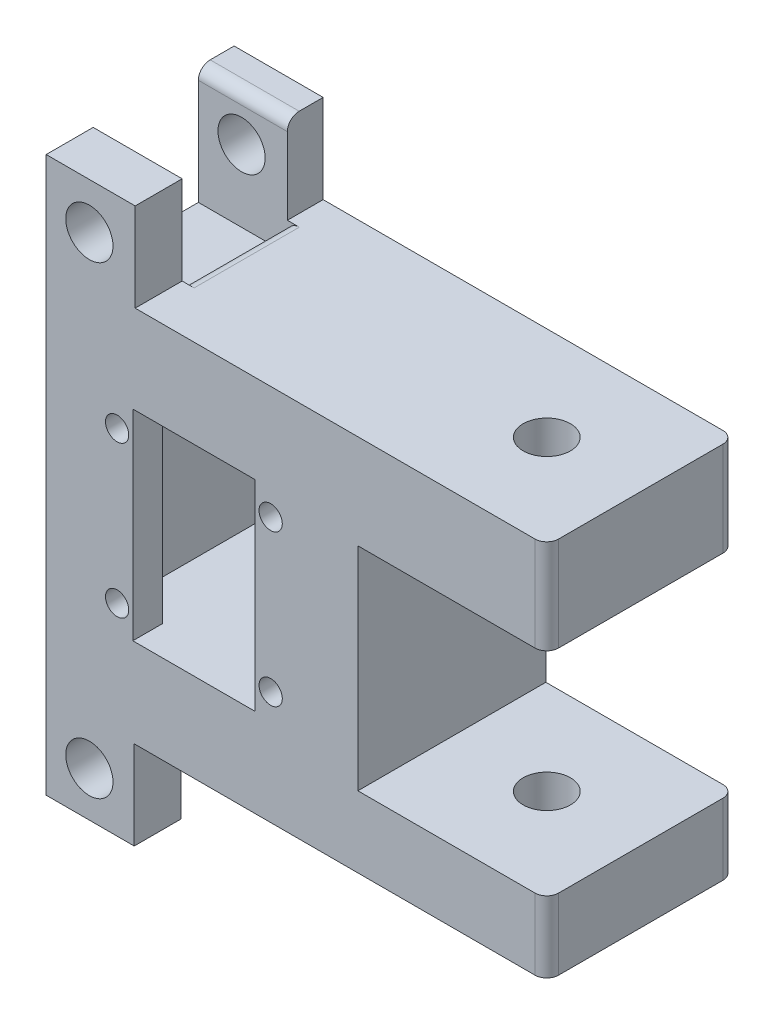
SolidWorks part; units mm, degrees
ref_plane "Front Plane" through (0, 0, 0) normal (0, 0, 1) x (1, 0, 0)
ref_plane "Top Plane" through (0, 0, 0) normal (0, 1, 0) x (1, 0, 0)
ref_plane "Right Plane" through (0, 0, 0) normal (1, 0, 0) x (0, 0, -1)
sketch "Sketch1" plane through (0, 0, 0) normal (0, 1, 0) x (1, 0, 0)
  line L1 (-53.8492, -20.2178) -> (53.8492, -20.2178)
  line L2 (-53.8492, -20.2178) -> (-53.8492, 20.2178)
  line L3 (-53.8492, 20.2178) -> (53.8492, 20.2178)
  line L4 (53.8492, -20.2178) -> (53.8492, 20.2178)
  line L5 (-53.8492, -20.2178) -> (53.8492, 20.2178) construction
  line L6 (-53.8492, 20.2178) -> (53.8492, -20.2178) construction
  point P0 (0, 0)
extrude "Boss-Extrude1" add sketch "Sketch1" along normal blind 55.88 and the other way blind 25.3849
sketch "Sketch7" plane through (0, 0, 20.2178) normal (0, 0, 1) x (1, 0, 0)
  line L0 (53.8492, 55.88) -> (0, -25.3849)
  line L1 (-53.8492, -25.3849) -> (53.8492, -25.3849) construction
  line L2 (0, -25.3849) -> (-53.8492, 55.88)
  line L3 (-53.8492, 55.88) -> (0, 55.88)
  line L4 (-53.8492, 55.88) -> (53.8492, 55.88) construction
  line L5 (0, 55.88) -> (-26.9246, 15.2475)
  line L6 (-26.9246, 15.2475) -> (-22.0715, 15.2475)
  line L7 (-22.0715, 15.2475) -> (5.0717, 15.2475)
  line L8 (-22.0715, 15.2475) -> (-38.3353, 15.2475)
  line L9 (-22.0715, 15.2475) -> (-22.0715, -6.3425)
  line L11 (-43.8885, 36.8375) -> (-0.2546, 36.8375)
  line L12 (-43.8885, 36.8375) -> (-43.8885, -6.3425)
  line L13 (-43.8885, -6.3425) -> (-0.2546, -6.3425)
  line L14 (-0.2546, 36.8375) -> (-0.2546, -6.3425)
  line L15 (-43.8885, 36.8375) -> (-0.2546, -6.3425) construction
  line L16 (-43.8885, -6.3425) -> (-0.2546, 36.8375) construction
extrude "Cut-Extrude8" cut sketch "Sketch7" against normal through all
sketch "Sketch11" plane through (0, -25.3849, 0) normal (0, -1, 0) x (-1, 0, 0)
  line L0 (-53.8492, -20.2178) -> (-53.8492, 0)
  line L1 (-53.8492, -20.2178) -> (-53.8492, 20.2178) construction
  line L2 (-53.8492, 0) -> (-33.6314, 20.2178)
  line L3 (-53.8492, 20.2178) -> (53.8492, 20.2178) construction
  line L4 (-33.6314, 20.2178) -> (-33.6314, 0)
  circle A0 centre (-33.6314, 0) radius 5.08
extrude "Cut-Extrude9" cut sketch "Sketch11" against normal through all
fillet "Fillet2" radius 2.54 2 edges at (53.8492, 15.2475, -20.2178) (53.8492, 15.2475, 20.2178)
sketch "Sketch12" plane through (53.8492, 0, 0) normal (1, 0, 0) x (0, 0, -1)
  line L0 (17.6778, 55.88) -> (17.6778, 15.2475)
  line L1 (17.6778, -25.3849) -> (17.6778, 55.88) construction
  line L2 (17.6778, 15.2475) -> (17.6778, 0)
  line L3 (17.6778, 15.2475) -> (-17.6778, 15.2475)
  line L4 (-17.6778, 55.88) -> (-17.6778, -25.3849) construction
sketch "Sketch13" plane through (0, 0, 20.2178) normal (0, 0, 1) x (1, 0, 0)
  line L0 (51.3092, 55.88) -> (51.3092, 15.2475)
  line L1 (51.3092, -25.3849) -> (51.3092, 55.88) construction
  line L2 (51.3092, 15.2475) -> (13.2092, 15.2475)
  line L3 (13.2092, 15.2475) -> (13.2092, -10.0808)
  line L5 (13.2092, -10.0808) -> (57.4473, -10.0808)
  line L6 (13.2092, -10.0808) -> (13.2092, 35.5638)
  line L7 (13.2092, 35.5638) -> (57.4473, 35.5638)
  line L8 (57.4473, -10.0808) -> (57.4473, 35.5638)
extrude "Cut-Extrude12" cut sketch "Sketch13" against normal through all contours L7 L6 L2 | L3 L5 L7 L2 | L5 L8 L7
sketch "Sketch14" plane through (0, 0, 20.2178) normal (0, 0, 1) x (1, 0, 0)
  line L0 (-53.8492, -25.3849) -> (-44.869, -16.4047)
  line L1 (-53.8492, 55.88) -> (-44.869, 46.8997)
  circle A0 centre (-44.869, -16.4047) radius 5.08
  circle A1 centre (-44.869, 46.8997) radius 5.08
sketch "Sketch16" plane through (0, 55.88, 0) normal (0, 1, 0) x (1, 0, 0)
  line L0 (-53.8492, -20.2178) -> (51.3092, -20.2178) construction
  line L1 (-53.8492, 20.2178) -> (-34.704, 20.2178)
  line L2 (-53.8492, 20.2178) -> (-53.8492, -20.2178)
  line L3 (-53.8492, -20.2178) -> (-34.704, -20.2178)
  line L4 (-34.704, 20.2178) -> (-34.704, -20.2178)
extrude "Boss-Extrude3" add sketch "Sketch16" along normal blind 19.05
sketch "Sketch17" plane through (0, -25.3849, 0) normal (0, -1, 0) x (1, 0, 0)
  line L0 (51.3092, -20.2178) -> (-53.8492, -20.2178) construction
  line L1 (-53.8492, 20.2178) -> (-34.9093, 20.2178)
  line L2 (-53.8492, 20.2178) -> (-53.8492, -20.2178)
  line L3 (-53.8492, -20.2178) -> (-34.9093, -20.2178)
  line L4 (-34.9093, 20.2178) -> (-34.9093, -20.2178)
extrude "Boss-Extrude4" add sketch "Sketch17" along normal blind 19.05
sketch "Sketch18" plane through (0, 0, 20.2178) normal (0, 0, 1) x (1, 0, 0)
  line L0 (-34.704, 74.93) -> (-44.5589, 65.0751)
  line L1 (-34.9093, -44.4349) -> (-44.5589, -34.7854)
  circle A0 centre (-44.5589, 65.0751) radius 5.08
  circle A1 centre (-44.5589, -34.7854) radius 5.08
extrude "Cut-Extrude14" cut sketch "Sketch18" against normal through all
sketch "Sketch19" plane through (-53.8492, 0, 0) normal (-1, 0, 0) x (0, 0, 1)
  line L0 (20.2178, -44.4349) -> (0, -44.4349)
  line L1 (20.2178, -44.4349) -> (-20.2178, -44.4349) construction
  line L2 (0, -44.4349) -> (0, -30.8364)
  line L3 (0, -30.8364) -> (-12.5235, -30.8364)
  line L4 (20.2178, 74.93) -> (0, 74.93)
  line L5 (-20.2178, 74.93) -> (20.2178, 74.93) construction
  line L6 (0, 74.93) -> (0, 62.3375)
  line L7 (0, 62.3375) -> (-12.5235, 62.3375)
  line L9 (-12.5235, 62.3375) -> (10.1089, 62.3375)
  line L10 (-12.5235, 62.3375) -> (-12.5235, 74.93)
  line L11 (-12.5235, 74.93) -> (10.1089, 74.93)
  line L12 (10.1089, 62.3375) -> (10.1089, 74.93)
  line L13 (-12.5235, -30.8364) -> (10.1089, -30.8364)
  line L14 (-12.5235, -30.8364) -> (-12.5235, -44.4349)
  line L15 (-12.5235, -44.4349) -> (10.1089, -44.4349)
  line L16 (10.1089, -30.8364) -> (10.1089, -44.4349)
  line M2 (20.2178, 74.93) -> (-20.2178, 74.93)
  line M4 (-20.2178, -44.4349) -> (20.2178, -44.4349)
extrude "Cut-Extrude15" cut sketch "Sketch19" against normal blind 19.05 contours L3 L14 L2 M4 | L16 L13 L2 M4 | L10 L7 L6 M2 | L9 L12 L4 L6
sketch "Sketch20" plane through (0, -30.8364, 0) normal (0, -1, 0) x (-1, 0, 0)
  line L0 (34.9093, -10.1089) -> (34.9093, 12.5235) construction
  line L1 (34.9093, -9.9866) -> (53.8492, -9.9866)
  line L2 (34.9093, -9.9866) -> (34.9093, 12.5235)
  line L3 (34.9093, 12.5235) -> (53.8492, 12.5235)
  line L4 (53.8492, -9.9866) -> (53.8492, 12.5235)
extrude "Cut-Extrude16" cut sketch "Sketch20" against normal blind 12.7
sketch "Sketch21" plane through (0, 62.3375, 0) normal (0, 1, 0) x (1, 0, 0)
  line L0 (-34.7992, 12.5235) -> (-40.2797, 12.5235) construction
  line L1 (-34.6746, 12.5235) -> (-53.8492, 12.5235)
  line L2 (-34.6746, 12.5235) -> (-34.6746, -10.1089)
  line L3 (-34.6746, -10.1089) -> (-53.8492, -10.1089)
  line L4 (-53.8492, 12.5235) -> (-53.8492, -10.1089)
sketch "Sketch22" plane through (-34.7992, 0, 0) normal (-1, 0, 0) x (0, 0, 1)
  line L1 (-12.5235, 62.3375) -> (10.1089, 62.3375)
  line L2 (-12.5235, 62.3375) -> (-12.5235, 74.93)
  line L3 (-12.5235, 74.93) -> (10.1089, 74.93)
  line L4 (10.1089, 62.3375) -> (10.1089, 74.93)
sketch "Sketch23" plane through (-34.7992, 0, 0) normal (-1, 0, 0) x (0, 0, 1)
  line L1 (10.1089, 74.93) -> (-12.5235, 74.93)
  line L2 (10.1089, 74.93) -> (10.1089, 62.3375)
  line L3 (10.1089, 62.3375) -> (-12.5235, 62.3375)
  line L4 (-12.5235, 74.93) -> (-12.5235, 62.3375)
extrude "Cut-Extrude19" cut sketch "Sketch23" against normal blind 12.7
sketch "Sketch24" plane through (0, 62.3375, 0) normal (0, 1, 0) x (1, 0, 0)
  line L1 (-34.6746, 12.5235) -> (-53.8492, 12.5235)
  line L2 (-34.6746, 12.5235) -> (-34.6746, -10.1089)
  line L3 (-34.6746, -10.1089) -> (-53.8492, -10.1089)
  line L4 (-53.8492, 12.5235) -> (-53.8492, -10.1089)
extrude "Cut-Extrude20" cut sketch "Sketch24" against normal blind 12.7
fillet "Fillet4" radius 2.54 2 edges at (-0.2546, 15.2475, -20.2178) (-44.2766, 74.93, -12.5235)
fillet "Fillet5" radius 2.54 2 edges at (-34.9093, -25.3849, -1.2685) (-34.6746, 55.88, -1.2073)
sketch "Sketch25" plane through (0, 0, 20.2178) normal (0, 0, 1) x (1, 0, 0)
  line L0 (-43.8885, -6.3425) -> (-0.2546, -6.3425) construction
  line L1 (-0.2546, 36.8375) -> (-8.8723, 36.8375)
  line L2 (-0.2546, 36.8375) -> (-0.2546, -6.3425)
  line L3 (-0.2546, -6.3425) -> (-8.8723, -6.3425)
  line L4 (-8.8723, 36.8375) -> (-8.8723, -6.3425)
extrude "Boss-Extrude5" add sketch "Sketch25" against normal blind 6.35
sketch "Sketch26" plane through (0, 0, 20.2178) normal (0, 0, 1) x (1, 0, 0)
  line L0 (-43.8885, -6.3425) -> (-8.8723, -6.3425) construction
  line L1 (-43.8885, 36.8375) -> (-35.214, 36.8375)
  line L2 (-43.8885, 36.8375) -> (-43.8885, -6.3425)
  line L3 (-43.8885, -6.3425) -> (-35.214, -6.3425)
  line L4 (-35.214, 36.8375) -> (-35.214, -6.3425)
extrude "Boss-Extrude6" add sketch "Sketch26" against normal blind 6.35
sketch "Sketch27" plane through (0, 0, 13.8678) normal (0, 0, -1) x (-1, 0, 0)
  line L0 (43.8885, -6.3425) -> (38.5852, -1.0392)
  line L1 (43.8885, 36.8375) -> (38.5852, 31.5342)
  line L2 (0.2546, -6.3425) -> (5.5579, -1.0392)
  line L3 (0.2546, 36.8375) -> (5.5579, 31.5342)
  circle A0 centre (5.5579, -1.0392) radius 2.5
  circle A1 centre (5.5579, 31.5342) radius 2.5
  circle A2 centre (38.5852, -1.0392) radius 2.5
  circle A3 centre (38.5852, 31.5342) radius 2.5
extrude "Cut-Extrude21" cut sketch "Sketch27" against normal blind 6.35
extrude "Cut-Extrude18" cut sketch "Sketch22" against normal blind 12.7
